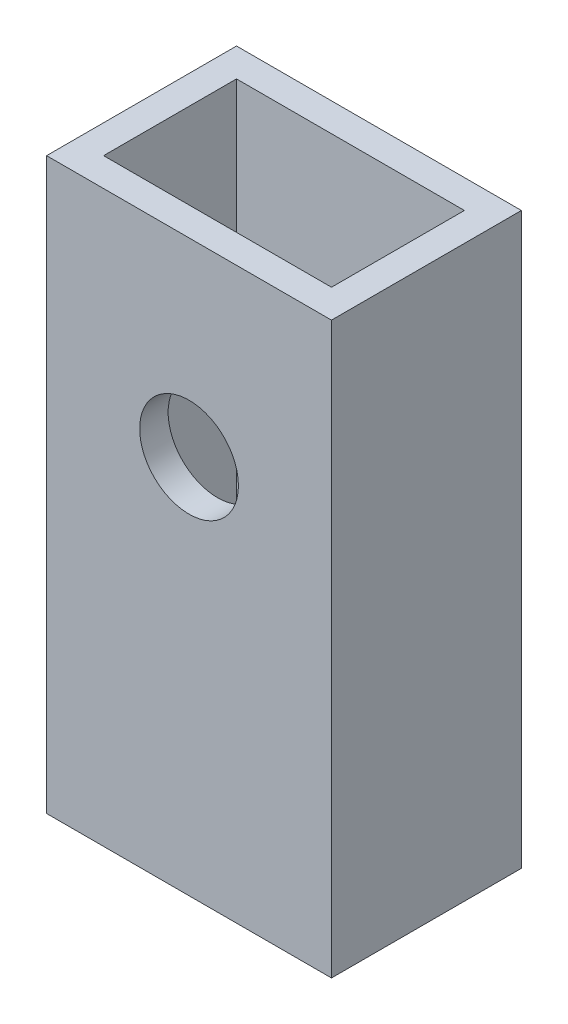
SolidWorks part; units mm, degrees
ref_plane "前视基准面" through (0, 0, 0) normal (0, 0, 1) x (1, 0, 0)
ref_plane "上视基准面" through (0, 0, 0) normal (0, 1, 0) x (1, 0, 0)
ref_plane "右视基准面" through (0, 0, 0) normal (1, 0, 0) x (0, 0, -1)
sketch "草图1" plane through (0, 0, 0) normal (0, 1, 0) x (1, 0, 0)
  line L1 (-7.5, 5) -> (7.5, 5)
  line L2 (-7.5, 5) -> (-7.5, -5)
  line L3 (-7.5, -5) -> (7.5, -5)
  line L4 (7.5, 5) -> (7.5, -5)
  line L5 (-7.5, 5) -> (7.5, -5) construction
  line L6 (-7.5, -5) -> (7.5, 5) construction
  point P0 (0, 0)
  dimension "D1" = 15
  dimension "D2" = 10
extrude "凸台-拉伸1" add sketch "草图1" along normal blind 30
sketch "草图2" plane through (0, 30, 0) normal (0, 1, 0) x (1, 0, 0)
  line L0 (7.5, 5) -> (-7.5, 5) construction
  line L1 (-6, 3.5) -> (6, 3.5)
  line L3 (-6, -3.5) -> (6, -3.5)
  line L4 (6, 3.5) -> (6, -3.5)
  line L5 (-6, 3.5) -> (-6, -3.5)
  line L6 (6, 0) -> (-8.0825, 0) construction
  line L7 (7.5, -5) -> (7.5, 5) construction
  line L9 (-7.5, 5) -> (-7.5, -5) construction
  point P0 (0, 0)
  dimension "D1" = 1.5
  dimension "D2" = 1.5
  dimension "D3" = 1.5
extrude "切除-拉伸1" cut sketch "草图2" against normal offset from surface (28.5 mm away) 1.5 up to face at (0, 0, 0)
sketch "草图3" plane through (0, 0, 5) normal (0, 0, 1) x (1, 0, 0)
  line L0 (-7.5, 20) -> (18.3665, 20) construction
  line L1 (-7.5, 30) -> (-7.5, 0) construction
  circle A0 centre (0, 20) radius 2.6
  dimension "D2" = 5.2
  dimension "D1" = 10
extrude "切除-拉伸2" cut sketch "草图3" against normal through all
sketch "草图4" plane through (0, 0, -5) normal (0, 0, -1) x (-1, 0, 0)
  circle A0 centre (0, 6.25) radius 1.6
  circle A1 centre (0, 20) radius 2.6 construction
  dimension "D1" = 13.75
  dimension "D2" = 3.2
extrude "切除-拉伸3" cut sketch "草图4" against normal blind 1.5
sketch "草图5" plane through (0, 0, 5) normal (0, 0, 1) x (1, 0, 0)
  circle A0 centre (0, 6.25) radius 3.25
  dimension "D1" = 6.5
